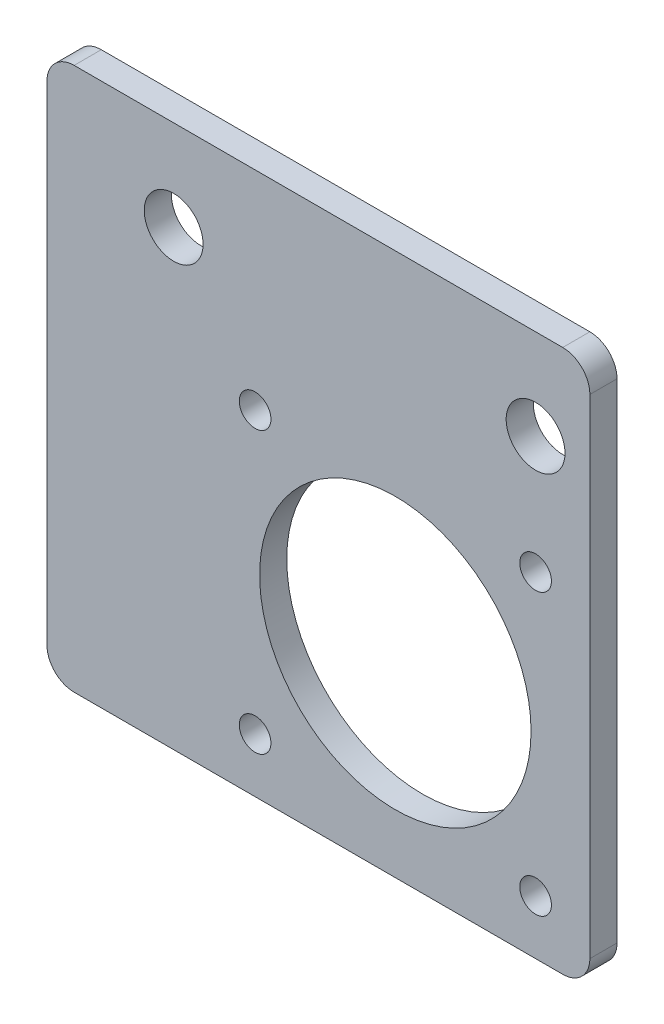
SolidWorks part; units mm, degrees
ref_plane "Ebene vorne" through (0, 0, 0) normal (0, 0, 1) x (1, 0, 0)
ref_plane "Ebene oben" through (0, 0, 0) normal (0, 1, 0) x (1, 0, 0)
ref_plane "Ebene rechts" through (0, 0, 0) normal (1, 0, 0) x (0, 0, -1)
sketch "Skizze1" plane through (0, 0, 0) normal (0, 0, 1) x (1, 0, 0)
  line L1 (30, 30) -> (-30, 30)
  line L2 (30, 30) -> (30, -30)
  line L3 (30, -30) -> (-30, -30)
  line L4 (-30, 30) -> (-30, -30)
  line L5 (30, 30) -> (-30, -30) construction
  line L6 (30, -30) -> (-30, 30) construction
  point P0 (0, 0)
  dimension "D1" = 60
  dimension "D2" = 60
extrude "Aufsatz-Linear austragen1" add sketch "Skizze1" along normal blind 3
fillet "Verrundung1" radius 3 4 edges at (-30, 30, 1.5) (30, 30, 1.5) (30, -30, 1.5) (-30, -30, 1.5)
sketch "Skizze2" plane through (0, 0, 3) normal (0, 0, 1) x (1, 0, 0)
  line L0 (-16, 20) -> (24, 20) construction
  line L1 (24, 7) -> (-7, 7) construction
  line L2 (24, 7) -> (24, -24) construction
  line L3 (24, -24) -> (-7, -24) construction
  line L4 (-7, 7) -> (-7, -24) construction
  line L5 (24, 7) -> (-7, -24) construction
  line L6 (24, -24) -> (-7, 7) construction
  line L8 (27, 30) -> (-27, 30) construction
  line L10 (-27, -30) -> (27, -30) construction
  line L11 (30, -27) -> (30, 27) construction
  line L12 (30, 13) -> (-13, 13) construction
  line L13 (30, 13) -> (30, -30) construction
  line L14 (30, -30) -> (-13, -30) construction
  line L15 (-13, 13) -> (-13, -30) construction
  line L16 (30, 13) -> (-13, -30) construction
  line L17 (30, -30) -> (-13, 13) construction
  circle A0 centre (-7, -24) radius 1.75
  circle A1 centre (-7, 7) radius 1.75
  circle A2 centre (24, 7) radius 1.75
  circle A3 centre (24, -24) radius 1.75
  circle A4 centre (24, 20) radius 3.25
  circle A5 centre (-16, 20) radius 3.25
  circle A6 centre (8.5, -8.5) radius 15
  point P0 (8.5, -8.5)
  point P15 (8.5, -8.5)
  dimension "D8" = 3.5
  dimension "D9" = 6.5
  dimension "D10" = 30
  dimension "D2" = 10
  dimension "D3" = 31
  dimension "D4" = 31
  dimension "D5" = 40
  dimension "D6" = 21.5
  dimension "D7" = 43
extrude "Schnitt-Linear austragen1" cut sketch "Skizze2" against normal blind 12
